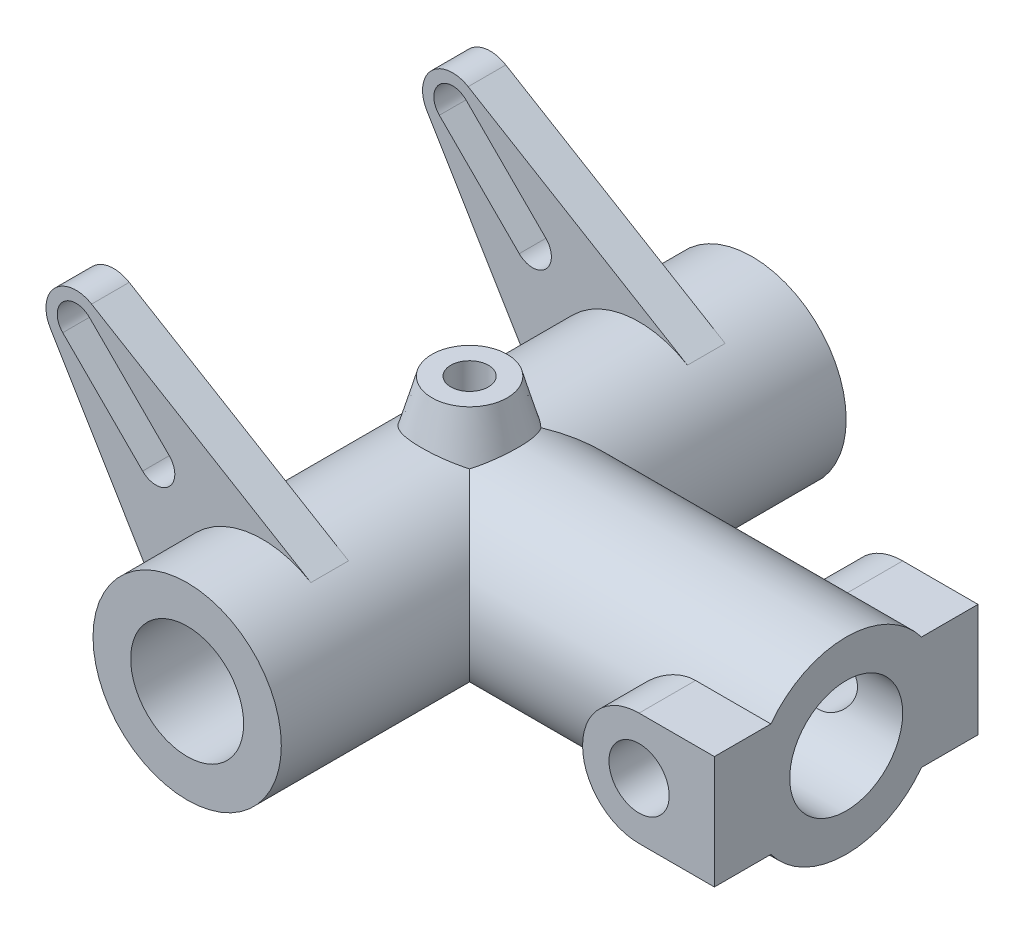
SolidWorks part; units mm, degrees
material "6061 Alloy"
ref_plane "Front Plane" through (0, 0, 0) normal (0, 0, 1) x (1, 0, 0)
ref_plane "Top Plane" through (0, 0, 0) normal (0, 1, 0) x (1, 0, 0)
ref_plane "Right Plane" through (0, 0, 0) normal (1, 0, 0) x (0, 0, -1)
sketch "Sketch1" plane through (0, 0, 0) normal (0, 0, 1) x (1, 0, 0)
  circle A0 centre (0, 0) radius 25
  dimension "D1" = 50
extrude "Boss-Extrude1" add sketch "Sketch1" along normal mid plane 150
sketch "Sketch2" plane through (0, 0, 75) normal (0, 0, 1) x (1, 0, 0)
  circle A0 centre (0, 0) radius 15
  dimension "D1" = 30
sketch "Sketch3" plane through (0, 0, 0) normal (0, 1, 0) x (1, 0, 0)
  circle A0 centre (0, 0) radius 10
  dimension "D1" = 20
extrude "Boss-Extrude2" add sketch "Sketch3" against normal blind 35 draft 16 from offset 35 draft outward yes
sketch "Sketch4" plane through (0, 0, 0) normal (1, 0, 0) x (0, 0, -1)
  circle A0 centre (0, 0) radius 25
  dimension "D1" = 50
extrude "Boss-Extrude3" add sketch "Sketch4" along normal blind 100
sketch "Sketch5" plane through (0, 0, 0) normal (0, 0, 1) x (1, 0, 0)
  line L0 (80, 15) -> (100, 15)
  line L1 (100, -25) -> (100, 25) construction
  line L2 (100, 15) -> (100, -15)
  line L3 (100, -15) -> (80, -15)
  arc A0 (80, 15) -> (80, -15) centre (80, 0) ccw
  point P6 (0, 0)
  dimension "D1" = 30
  dimension "D2" = 20
extrude "Boss-Extrude4" add sketch "Sketch5" along normal mid plane 70
ref_plane "Plane1" through (0, 0, 45) normal (0, 0, 1) x (1, 0, 0)
sketch "Sketch6" plane through (0, 0, 45) normal (0, 0, 1) x (1, 0, 0)
  line L0 (-56.3588, 45.3838) -> (-21.4416, -12.8553)
  line L1 (-45.3838, 56.3588) -> (12.8553, 21.4416)
  line L2 (-49.4975, 49.4975) -> (-28.2843, 28.2843) construction
  line L3 (-45.9619, 53.033) -> (-24.7487, 31.8198)
  line L4 (-53.033, 45.9619) -> (-31.8198, 24.7487)
  line L5 (-49.4975, 49.4975) -> (0, 0)
  line L6 (0, 0) -> (0, 49.0913) construction
  arc A0 (-45.3838, 56.3588) -> (-56.3588, 45.3838) centre (-49.4975, 49.4975) ccw
  circle A1 centre (0, 0) radius 25 construction
  arc A2 (0, -25) -> (9.477, 23.1341) centre (0, 0) ccw construction
  circle A3 centre (0, 0) radius 25
  arc A4 (-45.9619, 53.033) -> (-53.033, 45.9619) centre (-49.4975, 49.4975) ccw
  arc A5 (-31.8198, 24.7487) -> (-24.7487, 31.8198) centre (-28.2843, 28.2843) ccw
  point P12 (-38.8909, 38.8909)
  dimension "D1" = 8
  dimension "D2" = 5
  dimension "D3" = 30
  dimension "D4" = 40
  dimension "D5" = 45
extrude "Boss-Extrude5" add sketch "Sketch6" along normal blind 10
mirror "Mirror1" about plane through (0, 0, 0) normal (0, 0, 1) of "Boss-Extrude5"
extrude "Cut-Extrude2" cut sketch "Sketch2" against normal through all both and the other way through all
sketch "Sketch7" plane through (100, 0, 0) normal (1, 0, 0) x (0, 0, -1)
  circle A0 centre (0, 0) radius 15
  dimension "D1" = 30
extrude "Cut-Extrude3" cut sketch "Sketch7" against normal blind 100
sketch "Sketch8" plane through (0, 0, 35) normal (0, 0, 1) x (1, 0, 0)
  circle A0 centre (80, 0) radius 8
  point P2 (0, 0)
  point P4 (0, 0)
  dimension "D1" = 16
extrude "Cut-Extrude4" cut sketch "Sketch8" against normal through all both and the other way through all
sketch "Sketch9" plane through (0, 35, 0) normal (0, 1, 0) x (1, 0, 0)
  circle A0 centre (0, 0) radius 5
  dimension "D1" = 10
extrude "Cut-Extrude5" cut sketch "Sketch9" against normal blind 30
